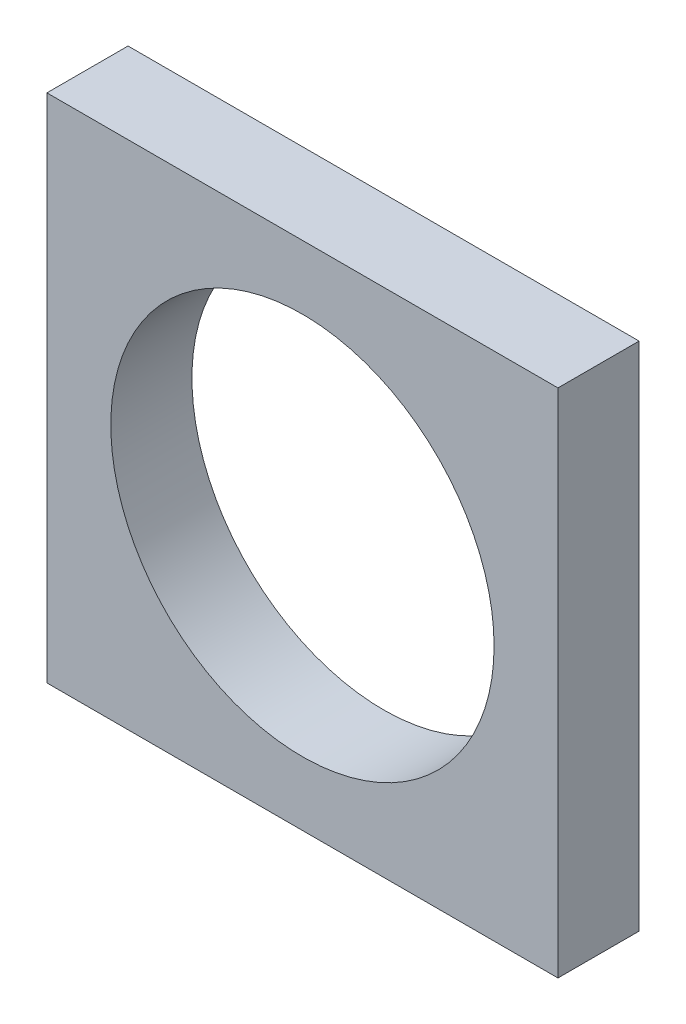
SolidWorks part; units mm, degrees
ref_plane "Front Plane" through (0, 0, 0) normal (0, 0, 1) x (1, 0, 0)
ref_plane "Top Plane" through (0, 0, 0) normal (0, 1, 0) x (1, 0, 0)
ref_plane "Right Plane" through (0, 0, 0) normal (1, 0, 0) x (0, 0, -1)
sketch "Sketch1" plane through (0, 0, 0) normal (0, 0, 1) x (1, 0, 0)
  line L1 (0, 0) -> (20, 0)
  line L2 (0, 0) -> (0, 20)
  line L3 (0, 20) -> (20, 20)
  line L4 (20, 0) -> (20, 20)
  line L5 (0, 0) -> (20, 20) construction
  line L6 (0, 20) -> (20, 0) construction
  point P4 (10, 10)
  dimension "D1" = 20
  dimension "D2" = 20
extrude "Boss-Extrude1" add sketch "Sketch1" along normal blind 3.175
sketch "Sketch3" plane through (0, 0, 3.175) normal (0, 0, 1) x (1, 0, 0)
  line L0 (0, 20) -> (20, 0) construction
  circle A0 centre (10, 10) radius 7.5
  dimension "D1" = 15
extrude "Cut-Extrude1" cut sketch "Sketch3" against normal blind 3.175
